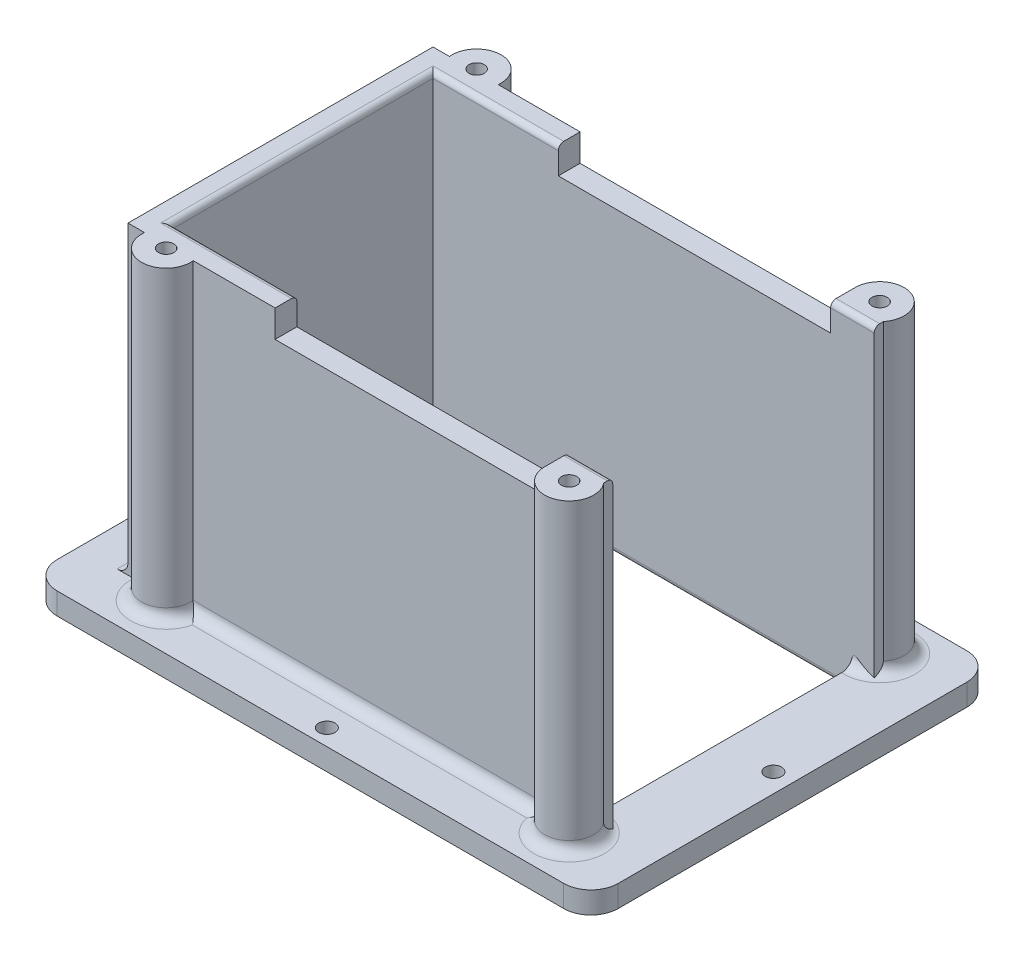
SolidWorks part; units mm, degrees
ref_plane "前视基准面" through (0, 0, 0) normal (0, 0, 1) x (1, 0, 0)
ref_plane "上视基准面" through (0, 0, 0) normal (0, 1, 0) x (1, 0, 0)
ref_plane "右视基准面" through (0, 0, 0) normal (1, 0, 0) x (0, 0, -1)
sketch "草图1" plane through (0, 0, 0) normal (0, 1, 0) x (1, 0, 0)
  line L1 (-51.5, 37) -> (51.5, 37)
  line L2 (-51.5, 37) -> (-51.5, -37)
  line L3 (-51.5, -37) -> (51.5, -37)
  line L4 (51.5, 37) -> (51.5, -37)
  line L5 (-51.5, 37) -> (51.5, -37) construction
  line L6 (-51.5, -37) -> (51.5, 37) construction
  point P0 (0, 0)
  dimension "D1" = 74
  dimension "D2" = 103
extrude "凸台-拉伸1" add sketch "草图1" along normal blind 4
sketch "草图2" plane through (0, 4, 0) normal (0, 1, 0) x (1, 0, 0)
  line L1 (-42.5, 28) -> (42.5, 28)
  line L2 (-42.5, 28) -> (-42.5, -28)
  line L3 (-42.5, -28) -> (42.5, -28)
  line L4 (42.5, 28) -> (42.5, -28)
  line L5 (-42.5, 28) -> (42.5, -28) construction
  line L6 (-42.5, -28) -> (42.5, 28) construction
  point P0 (0, 0)
  dimension "D1" = 56
  dimension "D2" = 85
extrude "凸台-拉伸2" add sketch "草图2" along normal blind 56
sketch "草图3" plane through (0, 60, 0) normal (0, 1, 0) x (1, 0, 0)
  line L1 (-42.5, 28) -> (-42.5, -28) construction
  line L2 (-38.5, 24) -> (42.5, 24)
  line L3 (-38.5, 24) -> (-38.5, -24)
  line L4 (-38.5, -24) -> (42.5, -24)
  line L5 (42.5, 24) -> (42.5, -24)
  line L6 (-42.5, -28) -> (42.5, -28) construction
  line L8 (42.5, 28) -> (-42.5, 28) construction
  line L9 (42.5, -28) -> (42.5, 28) construction
  dimension "D1" = 4
  dimension "D2" = 4
  dimension "D3" = 4
  dimension "D4" = 0
extrude "切除-拉伸1" cut sketch "草图3" against normal blind 56
sketch "草图7" plane through (0, 4, 0) normal (0, 1, 0) x (1, 0, 0)
  line L0 (2, 0) -> (10.6359, 0) construction
  line L1 (-35, 28.5) -> (39, 28.5)
  line L2 (-35, 28.5) -> (-35, -28.5)
  line L3 (-35, -28.5) -> (39, -28.5)
  line L4 (39, 28.5) -> (39, -28.5)
  line L5 (-35, 28.5) -> (39, -28.5) construction
  line L6 (-35, -28.5) -> (39, 28.5) construction
  line L7 (2, 0) -> (2, 8.4585) construction
  circle A0 centre (-35, 28.5) radius 4.5
  circle A1 centre (39, 28.5) radius 4.5
  circle A2 centre (39, -28.5) radius 4.5
  circle A3 centre (-35, -28.5) radius 4.5
  point P0 (2, 0)
  dimension "D3" = 9
  dimension "D1" = 74
  dimension "D2" = 57
  dimension "D4" = 0
  dimension "D5" = 2
extrude "凸台-拉伸3" add sketch "草图7" along normal blind 56 contours A0 | A3 | A2 | A1
sketch "草图8" plane through (0, 60, 0) normal (0, 1, 0) x (1, 0, 0)
  circle A0 centre (-35, 28.5) radius 1.4
  circle A1 centre (39, 28.5) radius 1.4
  circle A2 centre (-35, -28.5) radius 1.4
  circle A3 centre (39, -28.5) radius 1.4
  dimension "D1" = 2.8
  dimension "D2" = 2.8
  dimension "D3" = 2.8
  dimension "D4" = 2.8
extrude "切除-拉伸4" cut sketch "草图8" against normal through all
sketch "草图4" plane through (0, 4, 0) normal (0, 1, 0) x (1, 0, 0)
  line L0 (0, 0) -> (16.6497, 0) construction
  line L1 (0, 0) -> (0, 14.0662) construction
  circle A0 centre (-48, 0) radius 1.5
  circle A1 centre (48, 0) radius 1.5
  circle A2 centre (0, 34) radius 1.5
  circle A3 centre (0, -34) radius 1.5
  dimension "D1" = 3
  dimension "D4" = 3
  dimension "D2" = 96
  dimension "D3" = 0
  dimension "D5" = 68
  dimension "D6" = 0
extrude "切除-拉伸2" cut sketch "草图4" against normal through all
sketch "草图5" plane through (0, 4, 0) normal (0, 1, 0) x (1, 0, 0)
  line L1 (38.5, -24) -> (-38.5, -24)
  line L2 (38.5, -24) -> (38.5, 24)
  line L3 (38.5, 24) -> (-38.5, 24)
  line L4 (-38.5, -24) -> (-38.5, 24)
  line L5 (38.5, -24) -> (-38.5, 24) construction
  line L6 (38.5, 24) -> (-38.5, -24) construction
  point P0 (0, 0)
extrude "切除-拉伸3" cut sketch "草图5" against normal blind 26
fillet "圆角8" radius 2 8 edges at (40.2616, 4, -32.8195) (2, 4, -28) (-35, 4, -33) (-40.9861, 4, -28) (-42.5, 4, 0) (-35, 4, 33) (40.2616, 4, 32.8195) (2, 4, 28)
fillet "圆角7" radius 1 7 edges at (0, 0, -24) (-38.5, 0, 0) (38.5, 0, 0) (0, 0, 24) (2, 60, -24) (-38.5, 60, 0) (2, 60, 24)
sketch "草图9" plane through (0, 0, 0) normal (0, 0, 1) x (1, 0, 0)
  line L1 (-15.5, 60) -> (34.5, 60)
  line L2 (-15.5, 60) -> (-15.5, 55)
  line L3 (-15.5, 55) -> (34.5, 55)
  line L4 (34.5, 60) -> (34.5, 55)
  line L5 (-15.5, 60) -> (34.5, 55) construction
  line L6 (-15.5, 55) -> (34.5, 60) construction
  line L7 (-30.5279, 60) -> (34.5279, 60) construction
  line L8 (34.5, 60) -> (34.5, 6) construction
  point P0 (9.5, 57.5)
  dimension "D1" = 0
  dimension "D2" = 0
  dimension "D3" = 5
  dimension "D4" = 50
extrude "切除-拉伸5" cut sketch "草图9" against normal through all and the other way through all
fillet "圆角9" radius 5 4 edges at (-51.5, 2, 37) (-51.5, 2, -37) (51.5, 2, -37) (51.5, 2, 37)
